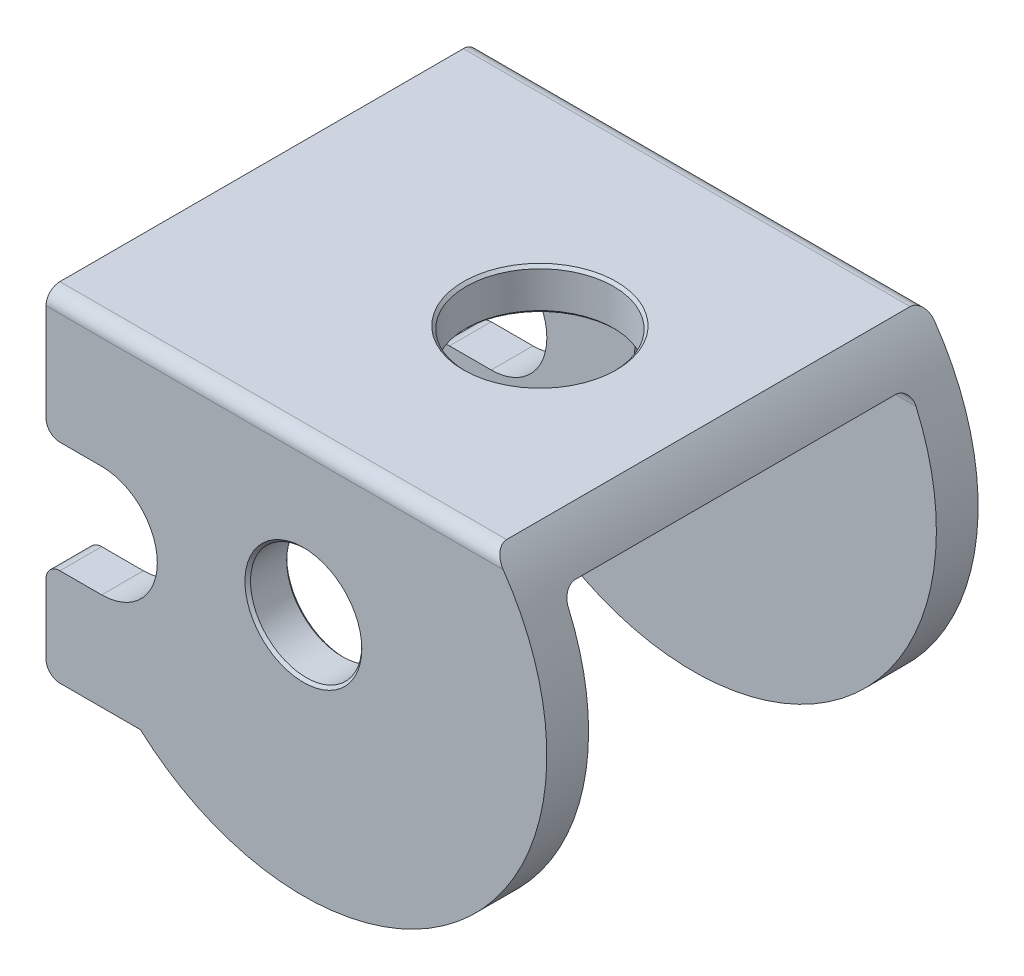
SolidWorks part; units mm, degrees
ref_plane "正面" through (0, 0, 0) normal (0, 0, 1) x (1, 0, 0)
ref_plane "平面" through (0, 0, 0) normal (0, 1, 0) x (1, 0, 0)
ref_plane "右側面" through (0, 0, 0) normal (1, 0, 0) x (0, 0, -1)
sketch "ｽｹｯﾁ1" plane through (0, 0, 0) normal (0, 0, 1) x (1, 0, 0)
  line L0 (-18.5, 11) -> (-18.5, -13)
  line L1 (-18.5, -13) -> (-11.7154, -13)
  line L2 (-18.5, 11) -> (13.6107, 11)
  arc A1 (-11.7154, -13) -> (13.6107, 11) centre (0, 0) ccw
  dimension "D4" = 11
  dimension "D3" = 18.5
  dimension "D2" = 35
  dimension "D1" = 24
extrude "ﾎﾞｽ - 押し出し1" add sketch "ｽｹｯﾁ1" along normal mid plane 31
sketch "ｽｹｯﾁ2" plane through (0, 0, 15.5) normal (0, 0, 1) x (1, 0, 0)
  line L0 (-18.5, 11) -> (-18.5, -13) construction
  line L1 (-18.5, 2) -> (-14.5, 2)
  line L2 (-18.5, 2) -> (-18.5, -6)
  line L3 (-18.5, -6) -> (-14.5, -6)
  line L5 (13.6107, 11) -> (-18.5, 11) construction
  arc A0 (-14.5, -6) -> (-14.5, 2) centre (-14.5, -2) ccw
  circle A1 centre (0, 0) radius 4
  point P10 (0, 0)
  point P13 (0, 0)
  dimension "D6" = 8
  dimension "D1" = 8
  dimension "D2" = 9
  dimension "D5" = 4
extrude "ｶｯﾄ - 押し出し1" cut sketch "ｽｹｯﾁ2" against normal through all
sketch "ｽｹｯﾁ3" plane through (-18.5, 0, 0) normal (-1, 0, 0) x (0, 0, 1)
  line L0 (-15.5, -17.5) -> (15.5, -17.5) construction
  line L1 (-12.5, 8) -> (12.5, 8)
  line L2 (-12.5, 8) -> (-12.5, -17.5)
  line L3 (-12.5, -17.5) -> (12.5, -17.5)
  line L4 (12.5, 8) -> (12.5, -17.5)
  line L5 (15.5, 11) -> (-15.5, 11) construction
  line L6 (15.5, -17.5) -> (15.5, 11) construction
  line L7 (-15.5, 11) -> (-15.5, -17.5) construction
  dimension "D1" = 3
  dimension "D2" = 3
  dimension "D3" = 3
extrude "ｶｯﾄ - 押し出し2" cut sketch "ｽｹｯﾁ3" against normal through all
sketch "ｽｹｯﾁ4" plane through (0, 11, 0) normal (0, 1, 0) x (1, 0, 0)
  line L1 (-18.5, -15.5) -> (-18.5, 15.5) construction
  circle A0 centre (1.5, 0) radius 5.3
  dimension "D1" = 20
  dimension "D3" = 10.6
extrude "ｶｯﾄ - 押し出し3" cut sketch "ｽｹｯﾁ4" against normal up to next
fillet "ﾌｨﾚｯﾄ1" radius 1 6 edges at (-18.5, -13, -14) (-18.5, -13, 14) (-18.5, -6, -14) (-18.5, -6, 14) (-18.5, 2, -14) (-18.5, 2, 14)
fillet "ﾌｨﾚｯﾄ2" radius 1 4 edges at (-1.4678, 8, -12.5) (-1.4678, 8, 12.5) (-2.4447, 11, -15.5) (-2.4447, 11, 15.5)
chamfer "面取り1" distance 0.2 angle 45 6 edges at (0, -4, 12.5) (4, 0, 15.5) (0, 4, -12.5) (4, 0, -15.5) (-3.8, 8, 0) (1.5, 11, 5.3)
